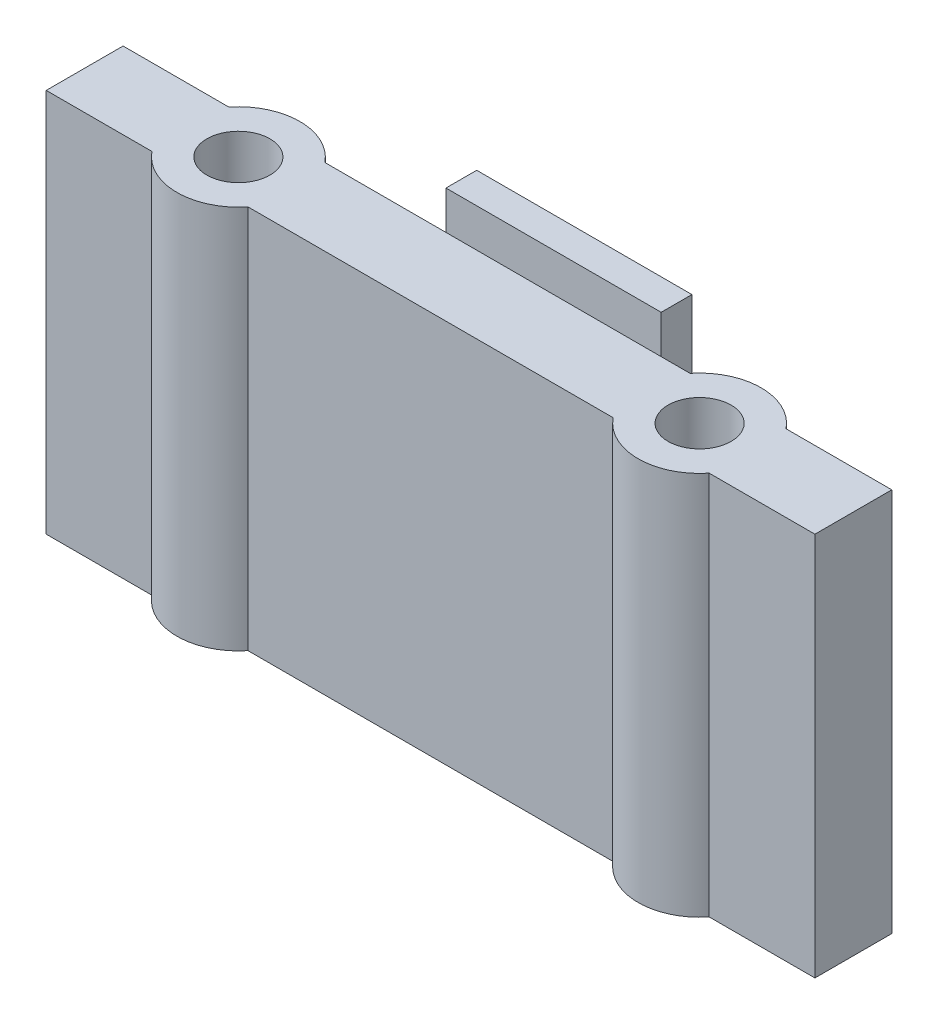
SolidWorks part; units mm, degrees
ref_plane "Front Plane" through (0, 0, 0) normal (0, 0, 1) x (1, 0, 0)
ref_plane "Top Plane" through (0, 0, 0) normal (0, 1, 0) x (1, 0, 0)
ref_plane "Right Plane" through (0, 0, 0) normal (1, 0, 0) x (0, 0, -1)
sketch "Sketch1" plane through (0, 0, 0) normal (0, 1, 0) x (1, 0, 0)
  line L0 (-15, 0) -> (15, 0) construction
  line L1 (-25, 2.5) -> (-18.1225, 2.5)
  line L2 (-25, 2.5) -> (-25, -2.5)
  line L3 (-25, -2.5) -> (-18.1225, -2.5)
  line L4 (25, 2.5) -> (25, -2.5)
  line L5 (-25, 2.5) -> (25, -2.5) construction
  line L6 (-25, -2.5) -> (25, 2.5) construction
  line L11 (-11.8775, 2.5) -> (11.8775, 2.5)
  line L12 (18.1225, 2.5) -> (25, 2.5)
  line L13 (18.1225, -2.5) -> (25, -2.5)
  line L14 (-11.8775, -2.5) -> (11.8775, -2.5)
  circle A0 centre (-15, 0) radius 2.05
  circle A1 centre (15, 0) radius 2.05
  arc A4 (11.8775, -2.5) -> (18.1225, -2.5) centre (15, 0) ccw
  arc A5 (-18.1225, -2.5) -> (-11.8775, -2.5) centre (-15, 0) ccw
  arc A6 (-11.8775, 2.5) -> (-18.1225, 2.5) centre (-15, 0) ccw
  arc A7 (18.1225, 2.5) -> (11.8775, 2.5) centre (15, 0) ccw
  point P0 (0, 0)
  point P9 (0, 0)
  dimension "D3" = 4.1
  dimension "D4" = 4.1
  dimension "D5" = 8
  dimension "D6" = 8
  dimension "D1" = 50
  dimension "D2" = 5
  dimension "D7" = 2.5
  dimension "D9" = 30
extrude "Boss-Extrude1" add sketch "Sketch1" along normal blind 25
sketch "Sketch2" plane through (0, 0, -2.5) normal (0, 0, -1) x (-1, 0, 0)
  line L1 (-7, 20.5) -> (7, 20.5)
  line L2 (-7, 20.5) -> (-7, 18.5)
  line L3 (-7, 18.5) -> (7, 18.5)
  line L4 (7, 20.5) -> (7, 18.5)
  line L7 (-11.8775, 25) -> (11.8775, 25) construction
  line L8 (-25, 25) -> (-25, 0) construction
  line L9 (25, 25) -> (25, 0) construction
  dimension "D1" = 6.5
  dimension "D2" = 2
  dimension "D3" = 18
  dimension "D4" = 18
  dimension "D5" = 18
extrude "Boss-Extrude2" add sketch "Sketch2" along normal blind 5
sketch "Sketch3" plane through (0, 20.5, 0) normal (0, 1, 0) x (1, 0, 0)
  line L0 (7, 7.5) -> (7, 2.5) construction
  line L1 (7, 5.5) -> (-7, 5.5)
  line L2 (7, 5.5) -> (7, 7.5)
  line L3 (7, 7.5) -> (-7, 7.5)
  line L4 (-7, 5.5) -> (-7, 7.5)
  dimension "D1" = 2
extrude "Boss-Extrude3" add sketch "Sketch3" along normal blind 4
sketch "Sketch4" plane through (-7, 0, 0) normal (-1, 0, 0) x (0, 0, 1)
  line L0 (-7.5, 18.5) -> (-2.5, 13.5)
  line L1 (-2.5, 25) -> (-2.5, 0) construction
  line L2 (-2.5, 25) -> (-2.5, 0) construction
  dimension "D1" = 45
rib "Rib3" sketch "Sketch4" sketch "Sketch4" thickness 14 extrusion direction parallel to sketch draft on no parameters "D1"=14
